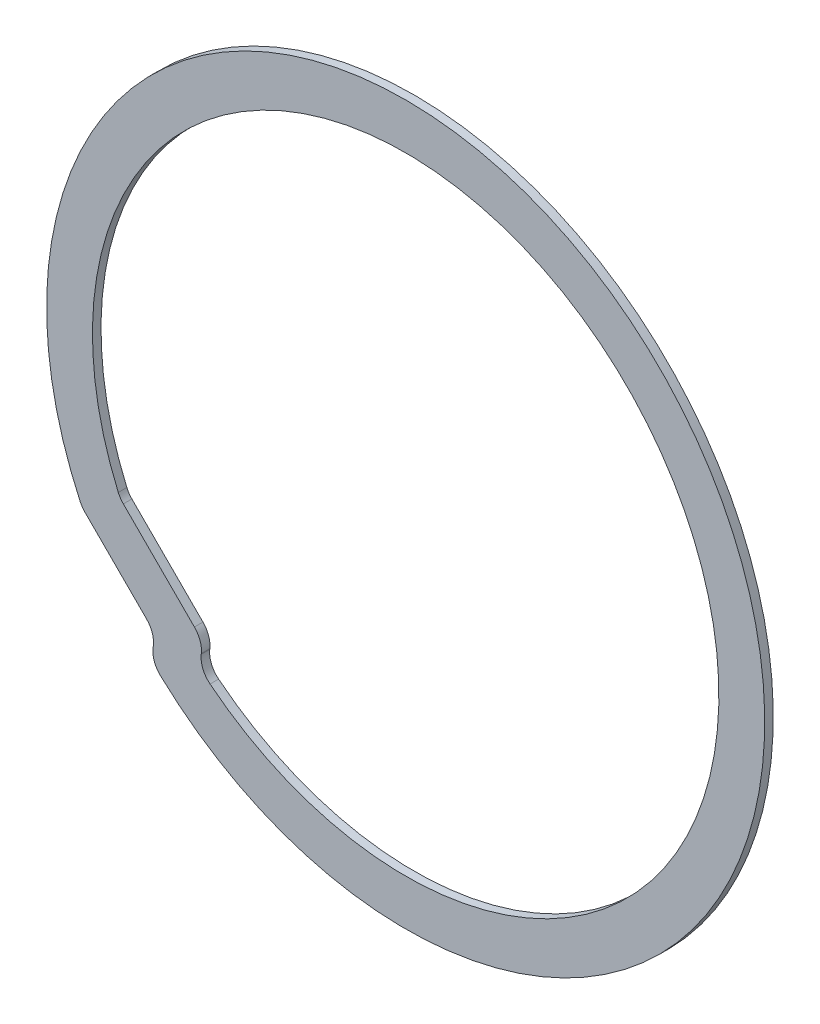
SolidWorks part; units mm, degrees
material "Balsa"
ref_plane "Front Plane" through (0, 0, 0) normal (0, 0, 1) x (1, 0, 0)
ref_plane "Top Plane" through (0, 0, 0) normal (0, 1, 0) x (1, 0, 0)
ref_plane "Right Plane" through (0, 0, 0) normal (1, 0, 0) x (0, 0, -1)
sketch "Sketch1" plane through (0, 0, 0) normal (0, 0, 1) x (1, 0, 0)
  line L0 (0, -110.0909) -> (0, -70.6286) construction
  line L1 (0, 0) -> (0, 245.1538) construction
  line L2 (0, 0) -> (0, 631.6453) construction
  line L3 (-120.188, -34.2725) -> (-93.2472, -61.2132)
  line L4 (0, 0) -> (-284.8905, 0) construction
  line L5 (-93.2472, -61.2132) -> (-94.2927, -70.7977)
  line L8 (-93.2472, -61.2132) -> (-57.7675, -96.693) construction
  arc A0 (-57.7675, -96.693) -> (-120.188, -34.2725) centre (0, 23.495) ccw
  arc A2 (-120.188, -34.2725) -> (-57.7675, -96.693) centre (0, 23.495) ccw construction
  arc A3 (-94.2927, -70.7977) -> (-57.7675, -96.693) centre (0, 23.495) ccw
  point P2 (0, 156.7839)
  point P3 (0, -109.8059)
  point P15 (-93.2472, -61.2132)
  dimension "D1" = 266.5898
  dimension "D2" = 266.7
  dimension "D3" = 23.495
  dimension "D5" = 109.22
  dimension "D6" = 45
  dimension "D7" = 38.1
extrude "Boss-Extrude1" add sketch "Sketch1" along normal mid plane 3.175
sketch "Sketch2" plane through (0, 0, 1.5875) normal (0, 0, 1) x (1, 0, 0)
  line L4 (-75.4449, -54.9485) -> (-76.4526, -64.187)
  line L5 (-106.033, -24.3603) -> (-75.4449, -54.9485)
  line L6 (-75.4449, -54.9485) -> (-76.4526, -64.187)
  line L7 (-106.033, -24.3603) -> (-75.4449, -54.9485)
  arc A2 (-76.4526, -64.187) -> (-106.033, -24.3603) centre (0, 23.495) ccw
  arc A3 (-76.4526, -64.187) -> (-106.033, -24.3603) centre (0, 23.495) ccw
  dimension "D1" = 17.018
extrude "Cut-Extrude1" cut sketch "Sketch2" against normal up to surface (3.175 mm away) up to face at (-30.5678, -4.3762, -1.5875)
fillet "Fillet1" radius 8.89 6 edges at (-106.033, -24.3603, 0) (-120.188, -34.2725, 0) (-94.2927, -70.7977, 0) (-93.2472, -61.2132, 0) (-75.4449, -54.9485, 0) (-76.4526, -64.187, 0)
